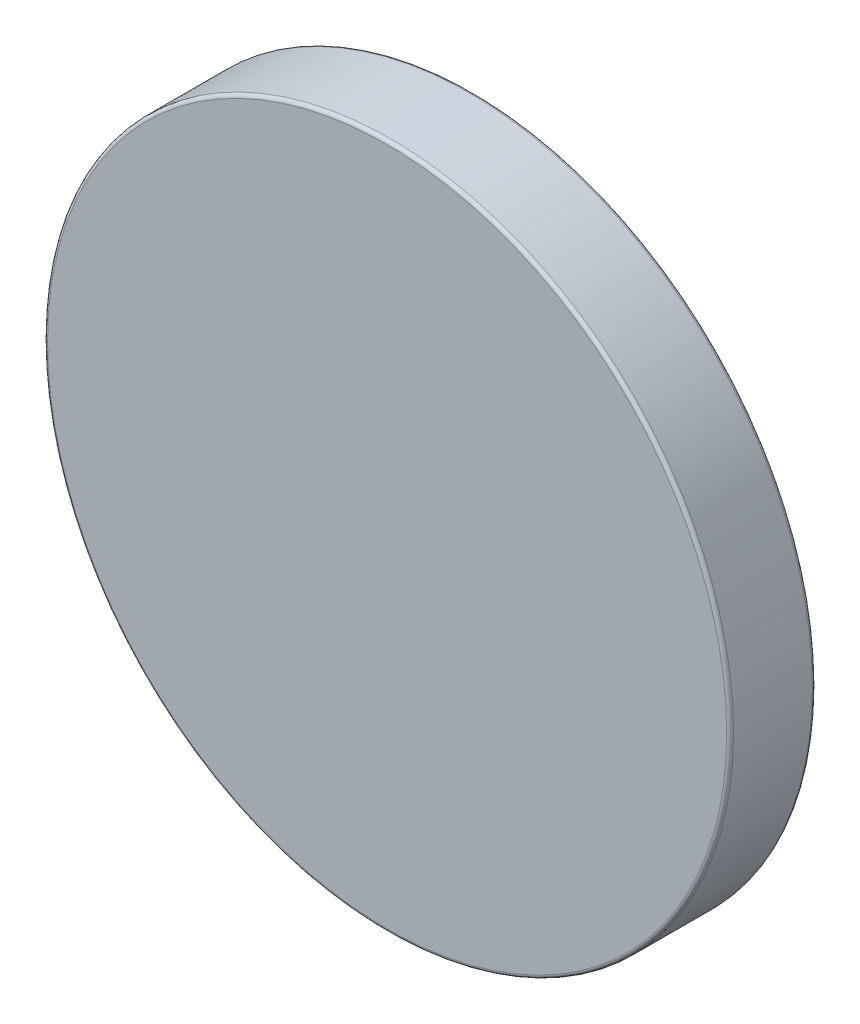
SolidWorks part; units mm, degrees
ref_plane "Front Plane" through (0, 0, 0) normal (0, 0, 1) x (1, 0, 0)
ref_plane "Top Plane" through (0, 0, 0) normal (0, 1, 0) x (1, 0, 0)
ref_plane "Right Plane" through (0, 0, 0) normal (1, 0, 0) x (0, 0, -1)
sketch "Sketch1" plane through (0, 0, 0) normal (0, 0, 1) x (1, 0, 0)
  circle A0 centre (0, 0) radius 12.7 construction
  dimension "OD" = 25.4
sketch "Sketch2" plane through (0, 0, 0) normal (1, 0, 0) x (0, 0, -1)
  line L0 (-1.5875, 0) -> (1.5875, 0) construction
  line L1 (0, 12.7) -> (0, -12.7) construction
  line L3 (-1.5875, 12.7) -> (1.5875, 12.7)
  line L4 (-1.5875, 12.7) -> (-1.5875, -12.7)
  line L5 (-1.5875, -12.7) -> (1.5875, -12.7)
  line L6 (1.5875, 12.7) -> (1.5875, -12.7)
  point P4 (0, 0)
  point P12 (0, 12.7)
  dimension "Thickness" = 3.175
sketch "Sketch3" plane through (0, 0, 0) normal (0, 0, 1) x (1, 0, 0)
  circle A0 centre (0, 0) radius 12.7 construction
  circle A1 centre (0, 0) radius 12.7
extrude "Boss-Extrude1" add sketch "Sketch3" along normal up to vertex (1.5875 mm away) and the other way up to vertex (1.5875 mm away) up to point (0, 12.7, 1.5875) other way up to point (0, 12.7, -1.5875)
fillet "Fillet1" radius 0.127 2 edges at (12.7, 0, -1.5875) (12.7, 0, 1.5875)
equation "\"Fillet@Fillet1\"=.005"
